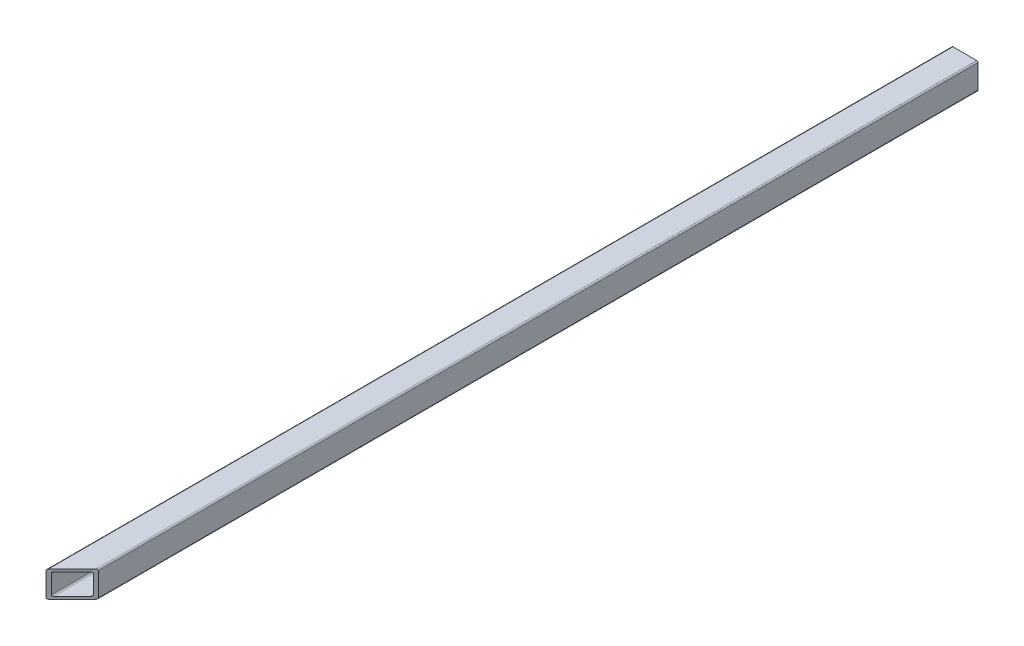
SolidWorks part; units mm, degrees
ref_plane "Plan de face" through (0, 0, 0) normal (0, 0, 1) x (1, 0, 0)
ref_plane "Plan de dessus" through (0, 0, 0) normal (0, 1, 0) x (1, 0, 0)
ref_plane "Plan de droite" through (0, 0, 0) normal (1, 0, 0) x (0, 0, -1)
sketch "Esquisse2" plane through (0, 0, 0) normal (0, 0, 1) x (1, 0, 0)
  line L0 (6, 4) -> (34, 4)
  line L1 (2, 0) -> (38, 0)
  line L2 (0, 2) -> (0, 38)
  line L3 (2, 40) -> (38, 40)
  line L4 (40, 2) -> (40, 38)
  line L5 (36, 6) -> (36, 34)
  line L6 (6, 36) -> (34, 36)
  line L7 (4, 6) -> (4, 34)
  line L8 (4, 4) -> (36, 4) construction
  line L9 (36, 4) -> (36, 36) construction
  line L10 (4, 36) -> (36, 36) construction
  line L11 (4, 4) -> (4, 36) construction
  line L12 (0, 0) -> (40, 0) construction
  line L13 (0, 0) -> (0, 40) construction
  line L14 (0, 40) -> (40, 40) construction
  line L15 (40, 0) -> (40, 40) construction
  arc A0 (34, 4) -> (36, 6) centre (34, 6) ccw
  arc A1 (36, 34) -> (34, 36) centre (34, 34) ccw
  arc A2 (6, 36) -> (4, 34) centre (6, 34) ccw
  arc A3 (4, 6) -> (6, 4) centre (6, 6) ccw
  arc A4 (2, 0) -> (0, 2) centre (2, 2) cw
  arc A5 (0, 38) -> (2, 40) centre (2, 38) cw
  arc A6 (38, 40) -> (40, 38) centre (38, 38) cw
  arc A7 (40, 2) -> (38, 0) centre (38, 2) cw
  point P24 (0, 0)
  dimension "D4" = 2
  dimension "D1" = 40
  dimension "D2" = 40
  dimension "D3" = 4
extrude "Boss.-Extru.1" add sketch "Esquisse2" along normal blind 1380
sketch "Esquisse3" plane through (0, 40, 0) normal (0, 1, 0) x (1, 0, 0)
  line L0 (0, -1380) -> (40, -1340)
  line L1 (38, -1380) -> (2, -1380) construction
  line L2 (40, -1380) -> (40, 0) construction
  line L3 (0, -1380) -> (40, -1380)
  line L4 (40, -1380) -> (40, -1340)
  dimension "D1" = 45
  dimension "D2" = 40
extrude "Enlèv. mat.-Extru.1" cut sketch "Esquisse3" against normal blind 70
